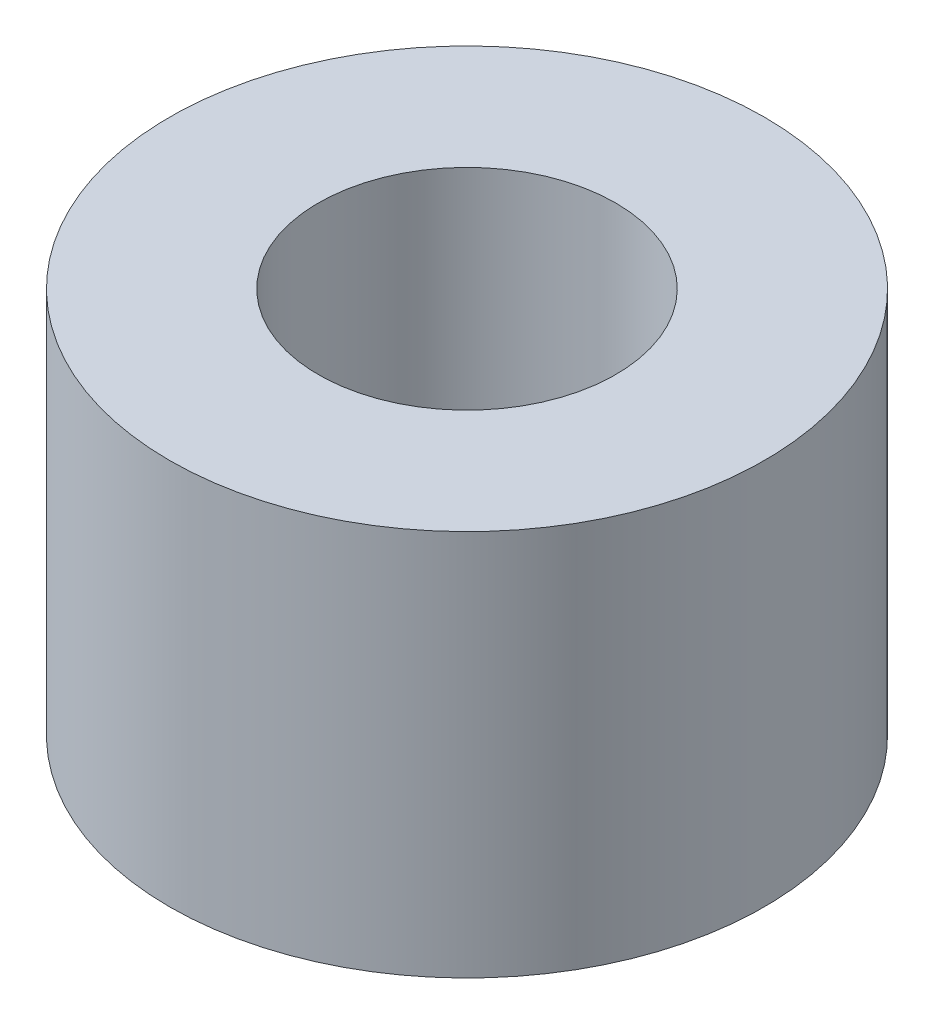
SolidWorks part; units mm, degrees
ref_plane "Front Plane" through (0, 0, 0) normal (0, 0, 1) x (1, 0, 0)
ref_plane "Top Plane" through (0, 0, 0) normal (0, 1, 0) x (1, 0, 0)
ref_plane "Right Plane" through (0, 0, 0) normal (1, 0, 0) x (0, 0, -1)
sketch "Sketch1" plane through (0, 0, 0) normal (0, 1, 0) x (1, 0, 0)
  circle A0 centre (0, 0) radius 5
  circle A1 centre (0, 0) radius 10
  dimension "D1" = 10
  dimension "D2" = 20
extrude "Boss-Extrude1" add sketch "Sketch1" along normal blind 13
